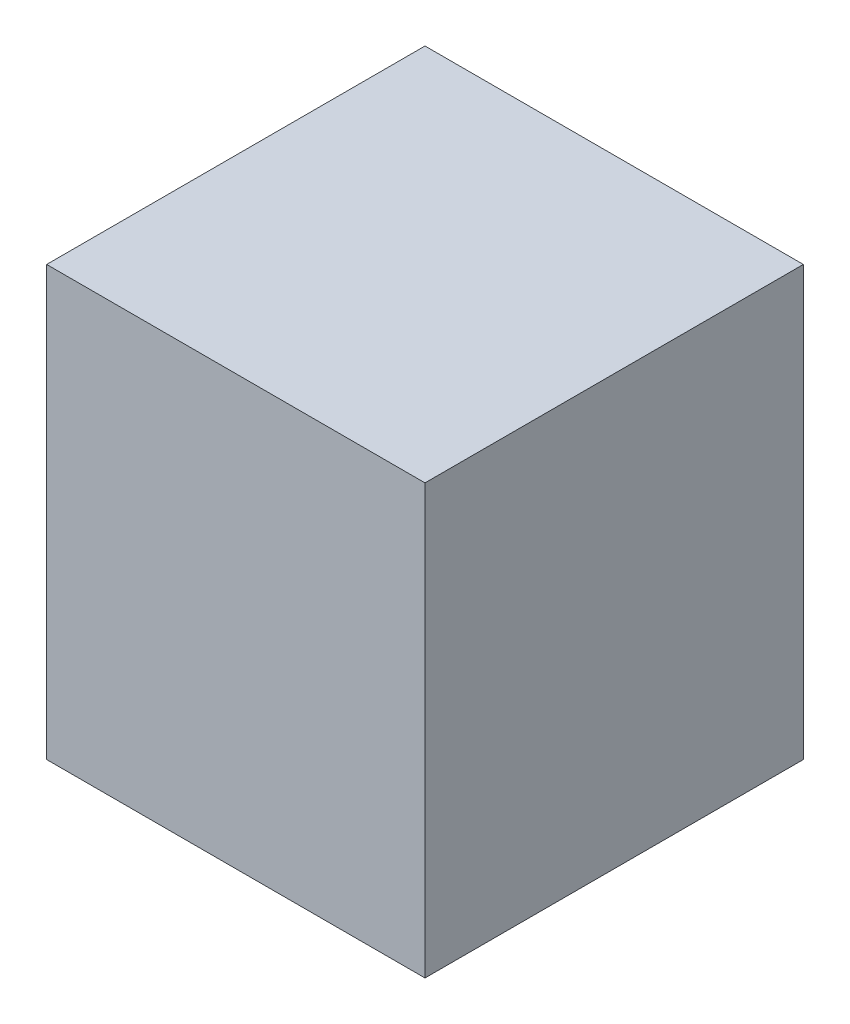
SolidWorks part; units mm, degrees
ref_plane "Front Plane" through (0, 0, 0) normal (0, 0, 1) x (1, 0, 0)
ref_plane "Top Plane" through (0, 0, 0) normal (0, 1, 0) x (1, 0, 0)
ref_plane "Right Plane" through (0, 0, 0) normal (1, 0, 0) x (0, 0, -1)
sketch "Sketch1" plane through (0, 0, 0) normal (0, 1, 0) x (1, 0, 0)
  line L1 (-23.1019, 14.1414) -> (36.8981, 14.1414)
  line L2 (-23.1019, 14.1414) -> (-23.1019, -45.8586)
  line L3 (-23.1019, -45.8586) -> (36.8981, -45.8586)
  line L4 (36.8981, 14.1414) -> (36.8981, -45.8586)
  dimension "D1" = 60
  dimension "D2" = 60
extrude "Boss-Extrude1" add sketch "Sketch1" along normal blind 68
